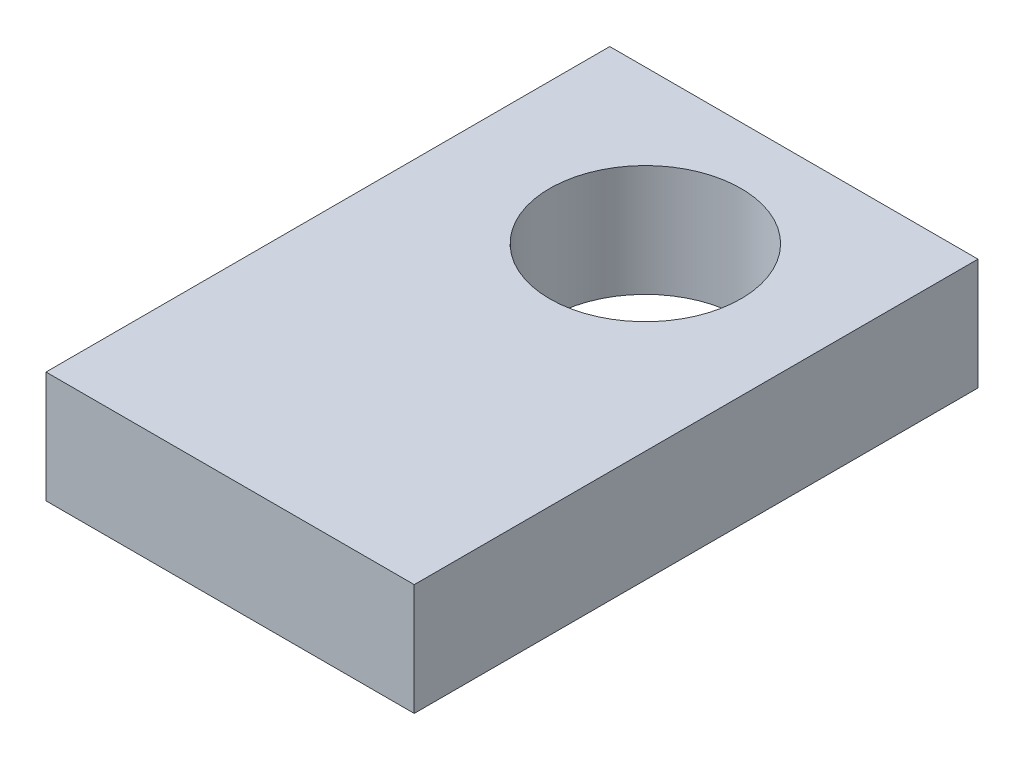
SolidWorks part; units mm, degrees
ref_plane "Ön Düzlem" through (0, 0, 0) normal (0, 0, 1) x (1, 0, 0)
ref_plane "Üst Düzlem" through (0, 0, 0) normal (0, 1, 0) x (1, 0, 0)
ref_plane "Sağ Düzlem" through (0, 0, 0) normal (1, 0, 0) x (0, 0, -1)
sketch "Çizim1" plane through (0, 0, 0) normal (0, 1, 0) x (1, 0, 0)
  line L1 (-20.6461, 36.1818) -> (25.5521, 36.1818)
  line L2 (-20.6461, 36.1818) -> (-20.6461, -34.5465)
  line L3 (-20.6461, -34.5465) -> (25.5521, -34.5465)
  line L4 (25.5521, 36.1818) -> (25.5521, -34.5465)
extrude "Yükseklik-Ekstrüzyon1" add sketch "Çizim1" along normal blind 14
sketch "Çizim2" plane through (0, 0, 0) normal (0, 1, 0) x (1, 0, 0)
  circle A0 centre (3, 17) radius 12
extrude "Kes-Ekstrüzyon1" cut sketch "Çizim2" along normal blind 15
